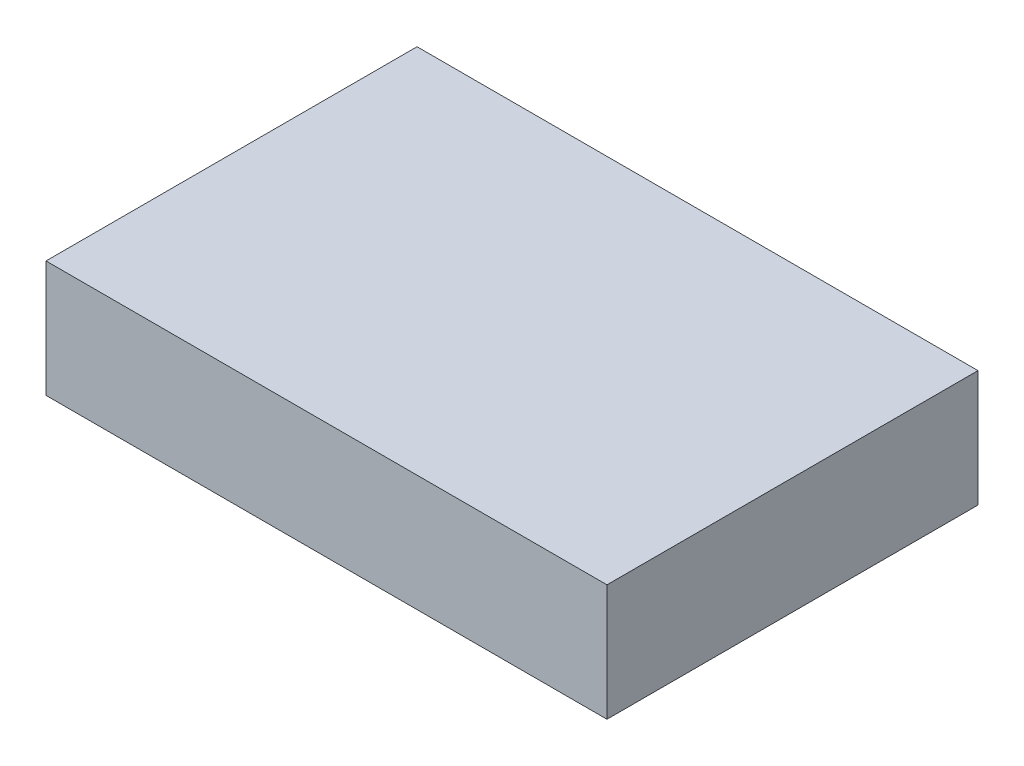
SolidWorks part; units mm, degrees
ref_plane "Front Plane" through (0, 0, 0) normal (0, 0, 1) x (1, 0, 0)
ref_plane "Top Plane" through (0, 0, 0) normal (0, 1, 0) x (1, 0, 0)
ref_plane "Right Plane" through (0, 0, 0) normal (1, 0, 0) x (0, 0, -1)
sketch "Sketch3" plane through (0, 0, 0) normal (0, 1, 0) x (1, 0, 0)
  line L1 (0, 0) -> (122.3539, 0)
  line L2 (0, 0) -> (0, 80.9293)
  line L3 (0, 80.9293) -> (122.3539, 80.9293)
  line L4 (122.3539, 0) -> (122.3539, 80.9293)
extrude "Extrude3" add sketch "Sketch3" against normal blind 25.4
